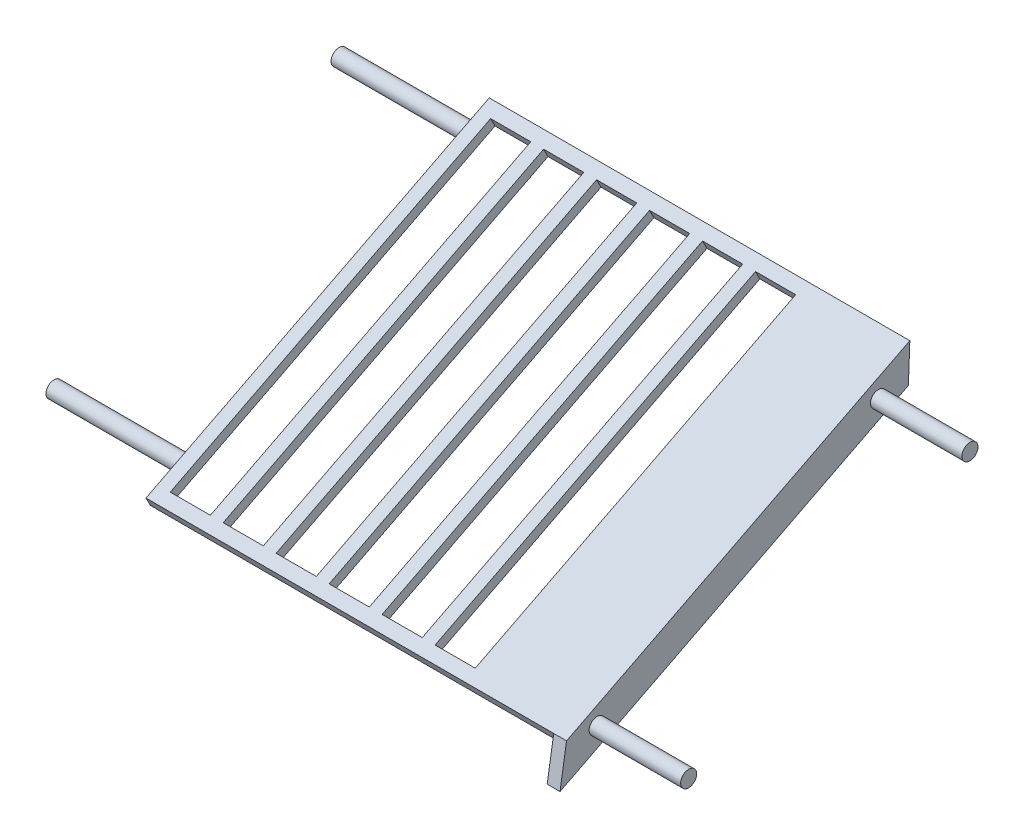
SolidWorks part; units mm, degrees
ref_plane "Front Plane" through (0, 0, 0) normal (0, 0, 1) x (1, 0, 0)
ref_plane "Top Plane" through (0, 0, 0) normal (0, 1, 0) x (1, 0, 0)
ref_plane "Right Plane" through (0, 0, 0) normal (1, 0, 0) x (0, 0, -1)
sketch "Sketch1" plane through (0, 0, 0) normal (1, 0, 0) x (0, 0, -1)
  line L1 (-35.6381, 26.8677) -> (1164.3619, 26.8677)
  line L2 (-35.6381, 26.8677) -> (-35.6381, -1473.1323)
  line L3 (-35.6381, -1473.1323) -> (1164.3619, -1473.1323)
  line L4 (1164.3619, 26.8677) -> (1164.3619, -1473.1323)
  dimension "D1" = 1200
  dimension "D2" = 1500
extrude "Boss-Extrude1" add sketch "Sketch1" along normal blind 160
sketch "Sketch2" plane through (0, 0, 0) normal (-1, 0, 0) x (0, 0, 1)
  line L0 (293.3871, -77.7236) -> (-775.8207, 467.065)
  line L1 (293.3871, -77.7236) -> (279.7674, -104.4538)
  line L2 (279.7674, -104.4538) -> (-789.4404, 440.3348)
  line L3 (-775.8207, 467.065) -> (-789.4404, 440.3348)
  line L4 (333.1381, -383.8235) -> (-736.0698, -928.6121)
  line L5 (-736.0698, -928.6121) -> (-722.4501, -955.3423)
  line L6 (-722.4501, -955.3423) -> (346.7578, -410.5537)
  line L7 (346.7578, -410.5537) -> (333.1381, -383.8235)
  dimension "D1" = 30
  dimension "D2" = 30
extrude "Boss-Extrude2" add sketch "Sketch2" along normal blind 1270
sketch "Sketch3" plane through (0, -466.202, 237.5418) normal (0, -0.891, 0.454) x (-1, 0, 0)
  line L0 (1270, 1077.424) -> (1270, -122.576) construction
  line L1 (1229.5663, -82.576) -> (1104.5663, -82.576)
  line L2 (1229.5663, -82.576) -> (1229.5663, 1037.424)
  line L3 (1229.5663, 1037.424) -> (1104.5663, 1037.424)
  line L4 (1104.5663, -82.576) -> (1104.5663, 1037.424)
  line L5 (1270, 1077.424) -> (0, 1077.424) construction
  line L6 (1270, -122.576) -> (0, -122.576) construction
  dimension "D1" = 40.4337
  dimension "D2" = 40
  dimension "D3" = 40
  dimension "D4" = 125
extrude "Cut-Extrude2" cut sketch "Sketch3" against normal blind 30
pattern_linear "LPattern1" count 6 spacing 165 along (1, 0, 0) of "Cut-Extrude2"
sketch "Sketch4" plane through (0, 30.2432, 15.4097) normal (0, -0.891, -0.454) x (-1, 0, 0)
  line L0 (1270, 903.3044) -> (1270, -296.6956) construction
  line L1 (1230, -256.6956) -> (1105, -256.6956)
  line L2 (1230, -256.6956) -> (1230, 863.3044)
  line L3 (1230, 863.3044) -> (1105, 863.3044)
  line L4 (1105, -256.6956) -> (1105, 863.3044)
  line L5 (1270, -296.6956) -> (0, -296.6956) construction
  line L6 (1270, 903.3044) -> (0, 903.3044) construction
  dimension "D1" = 40
  dimension "D2" = 40
  dimension "D3" = 40
  dimension "D4" = 125
extrude "Cut-Extrude3" cut sketch "Sketch4" against normal blind 30
pattern_linear "LPattern2" count 6 spacing 165 along (1, 0, 0) of "Cut-Extrude3"
sketch "Sketch5" plane through (0, 26.8677, 0) normal (0, 1, 0) x (1, 0, 0)
  line L1 (0, 1164.3619) -> (160, 1164.3619)
  line L2 (0, 1164.3619) -> (0, -35.6381)
  line L3 (0, -35.6381) -> (160, -35.6381)
  line L4 (160, 1164.3619) -> (160, -35.6381)
extrude "Cut-Extrude5" cut sketch "Sketch5" against normal blind 3200 and the other way blind 70
sketch "Sketch6" plane through (0, 0, 0) normal (1, 0, 0) x (0, 0, -1)
  line L0 (-293.3871, -77.7236) -> (-346.7578, -410.5537)
  line L1 (-346.7578, -410.5537) -> (722.4501, -955.3423)
  line L2 (722.4501, -955.3423) -> (775.8207, 467.065)
  line L3 (775.8207, 467.065) -> (-293.3871, -77.7236)
extrude "Boss-Extrude3" add sketch "Sketch6" along normal blind 40
sketch "Sketch7" plane through (40, 0, 0) normal (1, 0, 0) x (0, 0, -1)
  line L0 (-60.6847, 40.8442) -> (-13.6197, -51.5262)
  line L1 (775.8207, 467.065) -> (-293.3871, -77.7236) construction
  line L2 (-13.6197, -51.5262) -> (779.0062, 352.3369)
  line L3 (-13.6197, -51.5262) -> (-484.2324, -291.3153)
  line L4 (-484.2324, -291.3153) -> (-228.5574, -1565.8614)
  line L5 (-228.5574, -1565.8614) -> (1566.4575, -862.1278)
  line L6 (1566.4575, -862.1278) -> (779.0062, 352.3369)
  line M4 (-293.3871, -77.7236) -> (-346.7578, -410.5537)
  line M5 (-346.7578, -410.5537) -> (722.4501, -955.3423)
  line M6 (722.4501, -955.3423) -> (775.8207, 467.065)
  dimension "D1" = 103.6696
extrude "Cut-Extrude6" cut sketch "Sketch7" against normal blind 1622 contours L5 L6 L2 L3 L4 M6 M5 M4 | L2 L3 M4 M5 M6
sketch "Sketch8" plane through (40, 0, 0) normal (1, 0, 0) x (0, 0, -1)
  circle A0 centre (-198.0705, -84.5963) radius 25
  circle A1 centre (678.1637, 359.2694) radius 25
  dimension "D1" = 50
  dimension "D2" = 50
extrude "Boss-Extrude4" add sketch "Sketch8" along normal blind 284.9861
sketch "Sketch10" plane through (-1270, 0, 0) normal (-1, 0, 0) x (0, 0, 1)
  line L0 (-789.4404, 440.3348) -> (279.7674, -104.4538) construction
  circle A0 centre (-716.618, 403.2299) radius 25
  circle A1 centre (171.1762, -49.1238) radius 25
  dimension "D1" = 50
  dimension "D2" = 50
extrude "Boss-Extrude5" add sketch "Sketch10" along normal blind 408.5417
